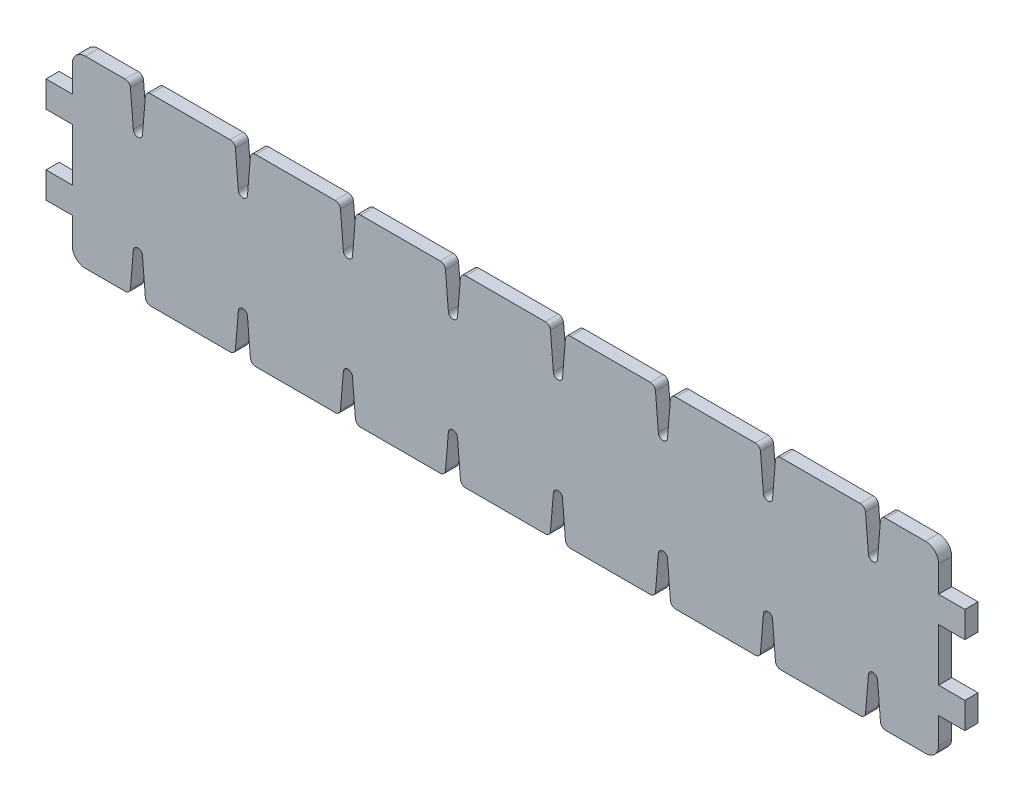
SolidWorks part; units mm, degrees
ref_plane "Front Plane" through (0, 0, 0) normal (0, 0, 1) x (1, 0, 0)
ref_plane "Top Plane" through (0, 0, 0) normal (0, 1, 0) x (1, 0, 0)
ref_plane "Right Plane" through (0, 0, 0) normal (1, 0, 0) x (0, 0, -1)
sketch "Sketch1" plane through (0, 0, 0) normal (0, 0, 1) x (1, 0, 0)
  line L0 (-90.218, 10) -> (299.3045, 10) construction
  line L1 (-75.8133, 35) -> (254.1867, 35)
  line L3 (-75.8133, -35) -> (254.1867, -35)
  line L5 (-85.8133, -10) -> (-75.8133, -10)
  line L6 (-91.3268, 0) -> (299.3045, 0) construction
  line L7 (-85.8133, 20) -> (-75.8133, 20)
  line L8 (-85.8133, 20) -> (-85.8133, 10)
  line L9 (-85.8133, 10) -> (-75.8133, 10)
  line L12 (-85.8133, -20) -> (-75.8133, -20)
  line L13 (-85.8133, -20) -> (-85.8133, -10)
  line L14 (89.1867, 30.0157) -> (89.1867, -45.8134) construction
  line L15 (-80.8133, 24.0051) -> (-80.8133, -32.23) construction
  line L16 (264.1867, -20) -> (264.1867, -10)
  line L17 (264.1867, -20) -> (254.1867, -20)
  line L19 (264.1867, -10) -> (254.1867, -10)
  line L20 (264.1867, 10) -> (254.1867, 10)
  line L22 (264.1867, 20) -> (254.1867, 20)
  line L23 (264.1867, 20) -> (264.1867, 10)
  line L24 (-75.8133, 20) -> (-75.8133, 35)
  line L25 (-75.8133, 10) -> (-75.8133, -10)
  line L26 (-75.8133, -35) -> (-75.8133, -20)
  line L27 (254.1867, -35) -> (254.1867, -20)
  line L28 (254.1867, 10) -> (254.1867, -10)
  line L29 (254.1867, 35) -> (254.1867, 20)
  point P6 (89.1867, -35)
  point P82 (-80.8133, 20)
  dimension "D5" = 330
  dimension "D1" = 70
  dimension "D3" = 20
  dimension "D4" = 10
  dimension "D7" = 10
extrude "Boss-Extrude1" add sketch "Sketch1" along normal blind 5
sketch "Sketch2" plane through (0, 0, 5) normal (0, 0, 1) x (1, 0, 0)
  line L0 (-50.8133, 26.1544) -> (-50.8133, -32.4929) construction
  line L1 (254.1867, 35) -> (-75.8133, 35) construction
  line L2 (254.1867, 35) -> (-75.8133, 35) construction
  line L3 (-53.8133, 35) -> (-47.8133, 35)
  line L4 (-53.8133, 35) -> (-52.5633, 20)
  line L6 (-47.8133, 35) -> (-49.0633, 20)
  line L7 (-86.9763, 0) -> (351.4175, 0) construction
  line L8 (-13.8133, 35) -> (-7.8133, 35)
  line L9 (-13.8133, 35) -> (-12.5633, 20)
  line L10 (-7.8133, 35) -> (-9.0633, 20)
  line L11 (26.1867, 35) -> (32.1867, 35)
  line L12 (26.1867, 35) -> (27.4367, 20)
  line L13 (32.1867, 35) -> (30.9367, 20)
  line L14 (66.1867, 35) -> (72.1867, 35)
  line L15 (66.1867, 35) -> (67.4367, 20)
  line L16 (72.1867, 35) -> (70.9367, 20)
  line L17 (106.1867, 35) -> (112.1867, 35)
  line L18 (106.1867, 35) -> (107.4367, 20)
  line L19 (112.1867, 35) -> (110.9367, 20)
  line L20 (146.1867, 35) -> (152.1867, 35)
  line L21 (146.1867, 35) -> (147.4367, 20)
  line L22 (152.1867, 35) -> (150.9367, 20)
  line L23 (186.1867, 35) -> (192.1867, 35)
  line L24 (186.1867, 35) -> (187.4367, 20)
  line L25 (192.1867, 35) -> (190.9367, 20)
  line L26 (226.1867, 35) -> (232.1867, 35)
  line L27 (226.1867, 35) -> (227.4367, 20)
  line L28 (232.1867, 35) -> (230.9367, 20)
  line L71 (232.1867, -35) -> (230.9367, -20)
  line L72 (226.1867, -35) -> (227.4367, -20)
  line L73 (226.1867, -35) -> (232.1867, -35)
  line L74 (192.1867, -35) -> (190.9367, -20)
  line L75 (186.1867, -35) -> (187.4367, -20)
  line L76 (186.1867, -35) -> (192.1867, -35)
  line L77 (152.1867, -35) -> (150.9367, -20)
  line L78 (146.1867, -35) -> (147.4367, -20)
  line L79 (146.1867, -35) -> (152.1867, -35)
  line L80 (112.1867, -35) -> (110.9367, -20)
  line L81 (106.1867, -35) -> (107.4367, -20)
  line L82 (106.1867, -35) -> (112.1867, -35)
  line L83 (72.1867, -35) -> (70.9367, -20)
  line L84 (66.1867, -35) -> (67.4367, -20)
  line L85 (66.1867, -35) -> (72.1867, -35)
  line L86 (32.1867, -35) -> (30.9367, -20)
  line L87 (26.1867, -35) -> (27.4367, -20)
  line L88 (26.1867, -35) -> (32.1867, -35)
  line L89 (-7.8133, -35) -> (-9.0633, -20)
  line L90 (-13.8133, -35) -> (-12.5633, -20)
  line L91 (-13.8133, -35) -> (-7.8133, -35)
  line L92 (-47.8133, -35) -> (-49.0633, -20)
  line L93 (-53.8133, -35) -> (-52.5633, -20)
  line L94 (-53.8133, -35) -> (-47.8133, -35)
  line L95 (-54.6736, 20) -> (-41.4603, 20) construction
  line L96 (-75.8133, 35) -> (-75.8133, 20) construction
  arc A0 (-52.5633, 20) -> (-49.0633, 20) centre (-50.8133, 20) ccw
  arc A1 (-12.5633, 20) -> (-9.0633, 20) centre (-10.8133, 20) ccw
  arc A2 (27.4367, 20) -> (30.9367, 20) centre (29.1867, 20) ccw
  arc A3 (67.4367, 20) -> (70.9367, 20) centre (69.1867, 20) ccw
  arc A4 (107.4367, 20) -> (110.9367, 20) centre (109.1867, 20) ccw
  arc A5 (147.4367, 20) -> (150.9367, 20) centre (149.1867, 20) ccw
  arc A6 (187.4367, 20) -> (190.9367, 20) centre (189.1867, 20) ccw
  arc A7 (227.4367, 20) -> (230.9367, 20) centre (229.1867, 20) ccw
  arc A22 (227.4367, -20) -> (230.9367, -20) centre (229.1867, -20) cw
  arc A23 (187.4367, -20) -> (190.9367, -20) centre (189.1867, -20) cw
  arc A24 (147.4367, -20) -> (150.9367, -20) centre (149.1867, -20) cw
  arc A25 (107.4367, -20) -> (110.9367, -20) centre (109.1867, -20) cw
  arc A26 (67.4367, -20) -> (70.9367, -20) centre (69.1867, -20) cw
  arc A27 (27.4367, -20) -> (30.9367, -20) centre (29.1867, -20) cw
  arc A28 (-12.5633, -20) -> (-9.0633, -20) centre (-10.8133, -20) cw
  arc A29 (-52.5633, -20) -> (-49.0633, -20) centre (-50.8133, -20) cw
  point P10 (-50.8133, 35)
  dimension "D5" = 15
  dimension "D1" = 25
  dimension "D2" = 6
  dimension "D3" = 8
  dimension "D4" = 3.5
extrude "Cut-Extrude1" cut sketch "Sketch2" against normal blind 5
fillet "Fillet1" radius 2 32 edges at (-47.8133, -35, 2.5) (-53.8133, -35, 2.5) (-7.8133, -35, 2.5) (-13.8133, -35, 2.5) (32.1867, -35, 2.5) (26.1867, -35, 2.5) (72.1867, -35, 2.5) (66.1867, -35, 2.5) (112.1867, -35, 2.5) (106.1867, -35, 2.5) (152.1867, -35, 2.5) (146.1867, -35, 2.5) (192.1867, -35, 2.5) (186.1867, -35, 2.5) (226.1867, -35, 2.5) (232.1867, -35, 2.5) (232.1867, 35, 2.5) (226.1867, 35, 2.5) (192.1867, 35, 2.5) (186.1867, 35, 2.5) (152.1867, 35, 2.5) (112.1867, 35, 2.5) (146.1867, 35, 2.5) (106.1867, 35, 2.5) (72.1867, 35, 2.5) (66.1867, 35, 2.5) (32.1867, 35, 2.5) (26.1867, 35, 2.5) (-7.8133, 35, 2.5) (-13.8133, 35, 2.5) (-53.8133, 35, 2.5) (-47.8133, 35, 2.5)
fillet "Congé1" radius 5 4 edges at (254.1867, -35, 2.5) (254.1867, 35, 2.5) (-75.8133, -35, 2.5) (-75.8133, 35, 2.5)
